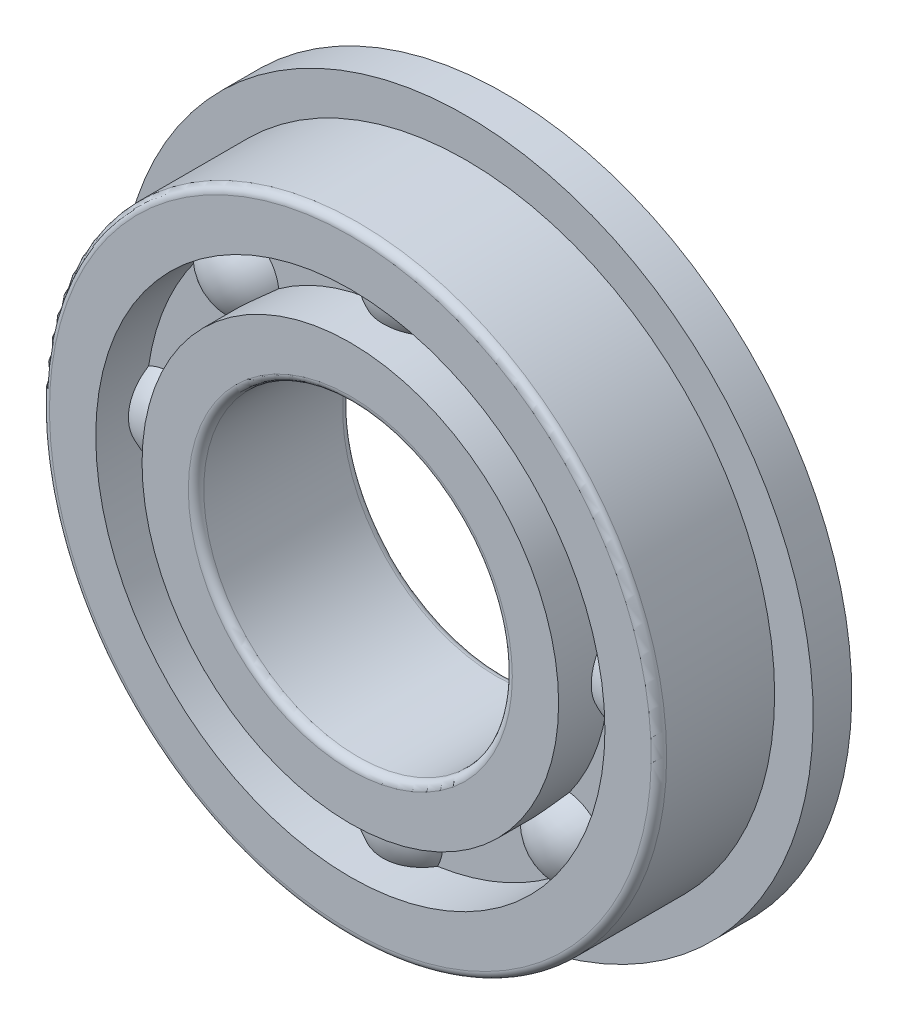
SolidWorks part; units mm, degrees
material "PW70:22:C1:0:1:2:Re:26:"
ref_plane "Front" through (0, 0, 0) normal (0, 0, 1) x (1, 0, 0)
ref_plane "Top" through (0, 0, 0) normal (0, 1, 0) x (1, 0, 0)
ref_plane "Side" through (0, 0, 0) normal (1, 0, 0) x (0, 0, -1)
sketch "Sketch1" plane through (0, 0, 0) normal (1, 0, 0) x (0, 0, -1)
  line L0 (0, 0) -> (0, 4) construction
  line L1 (0.7, 6.6) -> (2, 6.6)
  line L2 (-2, 4) -> (2, 4)
  line L3 (-2, 4) -> (-2, 5.4)
  line L4 (-2, 5.4) -> (-0.7, 5.4)
  line L5 (2, 4) -> (2, 5.4)
  line L6 (-2, 8) -> (2, 8)
  line L7 (-2, 8) -> (-2, 6.6)
  line L8 (-2, 6.6) -> (-0.7, 6.6)
  line L9 (2, 8) -> (2, 6.6)
  line L10 (0.7, 5.4) -> (2, 5.4)
  line L11 (-0.7, 6.6) -> (-0.7, 5.4)
  line L12 (0, 0) -> (-3, 0) construction
  line L13 (0.7, 6.6) -> (0.7, 5.4)
  line L14 (-0.7, 6.6) -> (0.7, 6.6) construction
  line L15 (-0.7, 5.4) -> (0.7, 5.4) construction
  line L16 (0, 7.3) -> (0, 4.7)
  line L17 (-2, 7.3) -> (2, 7.3) construction
  line L18 (0, 4) -> (0, 8) construction
  line L19 (1, 8) -> (1, 9)
  line L20 (1, 9) -> (2, 9)
  arc A0 (0, 4.7) -> (0, 7.3) centre (0, 6) ccw
  arc A1 (0, 4.71) -> (0, 7.29) centre (0, 6) ccw
  dimension "D1" = 0.01
  dimension "shaft" = 8
  dimension "D2" = 1
  dimension "housing" = 16
  dimension "D3" = 18
  dimension "width" = 4
  dimension "gap" = 1.2
sketch "Sketch2" plane through (0, 0, 0) normal (1, 0, 0) x (0, 0, -1)
  line L0 (0.7, 5.4) -> (2, 5.4) construction
  line L1 (2, 4) -> (2, 5.4) construction
  line L2 (-2, 4) -> (2, 4) construction
  line L3 (-2, 4) -> (-2, 5.4) construction
  line L4 (-2, 5.4) -> (-0.7, 5.4) construction
  line L5 (-2, 6.6) -> (-0.7, 6.6) construction
  line L6 (-0.7, 6.6) -> (-0.7, 5.4) construction
  line L7 (0.7, 6.6) -> (0.7, 5.4) construction
  line L8 (0.7, 6.6) -> (2, 6.6) construction
  line L9 (2, 8) -> (2, 6.6) construction
  line L10 (-2, 8) -> (2, 8) construction
  line L11 (-2, 8) -> (-2, 6.6) construction
  line L12 (0.7, 5.4) -> (2, 5.4)
  line L13 (2, 4) -> (2, 5.4)
  line L14 (-2, 4) -> (2, 4)
  line L15 (-2, 4) -> (-2, 5.4)
  line L16 (-2, 5.4) -> (-0.7, 5.4)
  line L17 (-2, 6.6) -> (-0.7, 6.6)
  line L18 (-0.7, 6.6) -> (-0.7, 5.4)
  line L19 (0.7, 6.6) -> (0.7, 5.4)
  line L20 (0.7, 6.6) -> (2, 6.6)
  line L21 (2, 9) -> (2, 6.6)
  line L22 (-2, 8) -> (1, 8)
  line L23 (-2, 8) -> (-2, 6.6)
  line L24 (-2, 0) -> (2, 0) construction
  line L25 (0, 0) -> (-3, 0) construction
  line L26 (1, 9) -> (2, 9) construction
  line L27 (1, 8) -> (1, 9) construction
  line L28 (1, 9) -> (2, 9)
  line L29 (1, 8) -> (1, 9)
revolve "Base-Revolve" add sketch "Sketch2" angle 360 about L24
sketch "Sketch4" plane through (0, 0, 0) normal (1, 0, 0) x (0, 0, -1)
  line L0 (0, 7.3) -> (0, 4.7) construction
  line L1 (0, 7.3) -> (0, 4.7)
  line L2 (0, 4.7) -> (0, 0) construction
  arc A0 (0, 4.7) -> (0, 7.3) centre (0, 6) ccw construction
  arc A1 (0, 4.7) -> (0, 7.3) centre (0, 6) ccw
revolve "Boss-Revolve1" add sketch "Sketch4" angle 360 about L2
sketch "Sketch5" plane through (0, 0, 0) normal (1, 0, 0) x (0, 0, -1)
  line L0 (0, 7.3) -> (0, 4.7) construction
  line L1 (0, 7.29) -> (0, 4.71)
  line L2 (0, 4.71) -> (0, 0) construction
  arc A0 (0, 4.71) -> (0, 7.29) centre (0, 6) ccw construction
  arc A1 (0, 4.71) -> (0, 7.29) centre (0, 6) ccw
revolve "Cut-Revolve1" cut sketch "Sketch5" angle 360 about L2
pattern_circular "CirPattern1" count 8 over 360 about axis through (0, 0, 0) along (0, 0, 1) of "Boss-Revolve1", "Cut-Revolve1"
fillet "Fillet1" radius 0.2 3 edges at (0, -4, -2) (0, -4, 2) (0, -8, 2)
